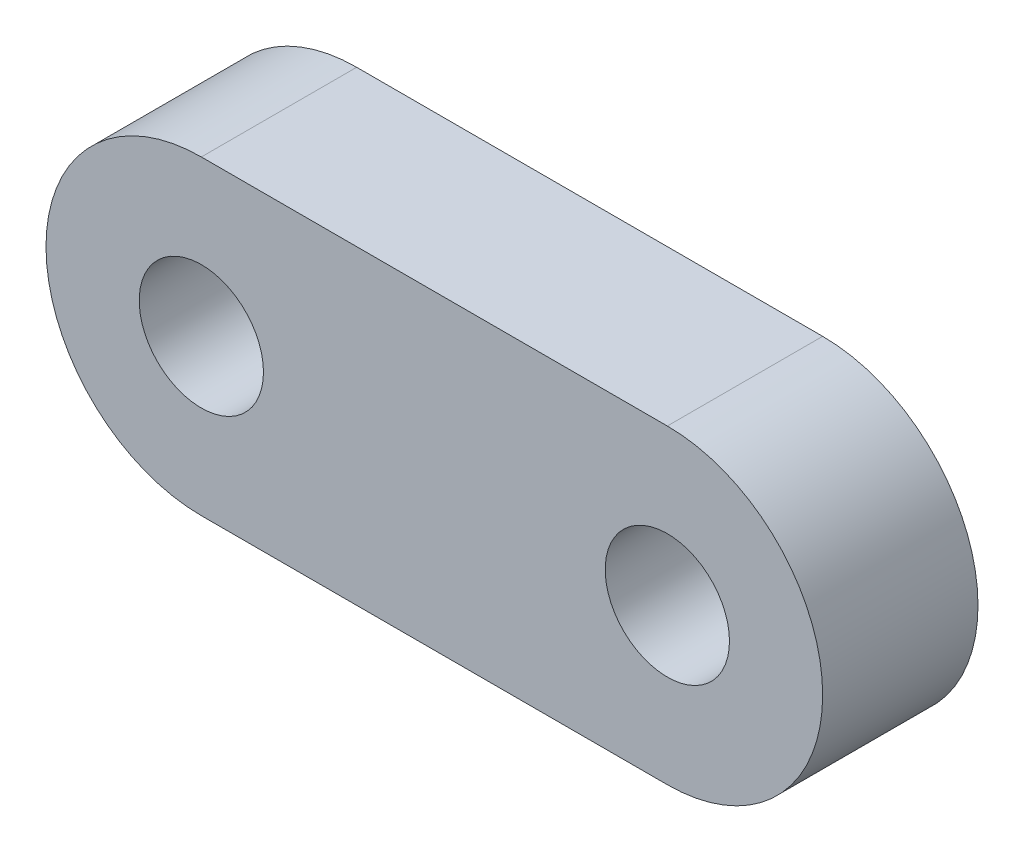
SolidWorks part; units mm, degrees
ref_plane "前基準面" through (0, 0, 0) normal (0, 0, 1) x (1, 0, 0)
ref_plane "上基準面" through (0, 0, 0) normal (0, 1, 0) x (1, 0, 0)
ref_plane "右基準面" through (0, 0, 0) normal (1, 0, 0) x (0, 0, -1)
sketch "草圖2" plane through (0, 0, 0) normal (0, 0, 1) x (1, 0, 0)
  line L0 (-7.5, 0) -> (7.5, 0) construction
  line L1 (-7.5, 5) -> (7.5, 5)
  line L2 (-7.5, -5) -> (7.5, -5)
  arc A0 (-7.5, 5) -> (-7.5, -5) centre (-7.5, 0) ccw
  arc A1 (7.5, -5) -> (7.5, 5) centre (7.5, 0) ccw
  circle A2 centre (7.5, 0) radius 2
  circle A3 centre (-7.5, 0) radius 2
  point P2 (0, 0)
  dimension "D2" = 4
  dimension "D3" = 5
  dimension "D1" = 15
extrude "填料-伸長1" add sketch "草圖2" along normal mid plane 5
